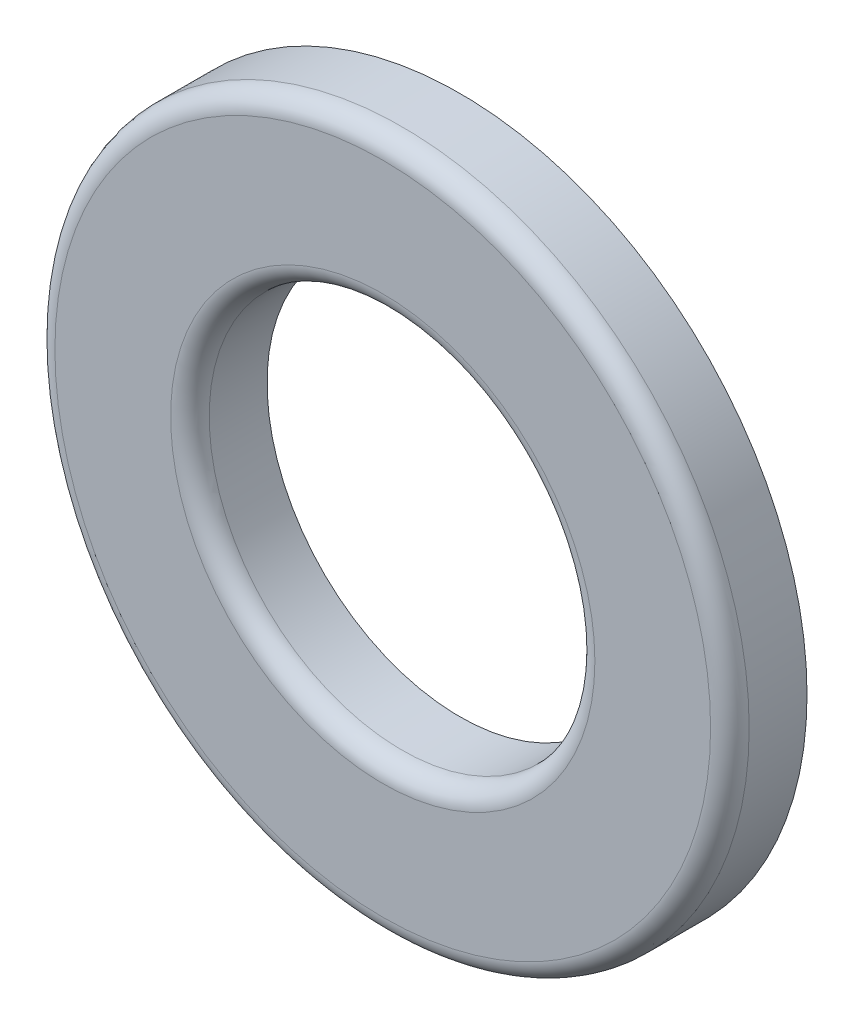
SolidWorks part; units mm, degrees
material "Chrome Stainless Steel"
ref_plane "Front Plane" through (0, 0, 0) normal (0, 0, 1) x (1, 0, 0)
ref_plane "Top Plane" through (0, 0, 0) normal (0, 1, 0) x (1, 0, 0)
ref_plane "Right Plane" through (0, 0, 0) normal (1, 0, 0) x (0, 0, -1)
sketch "Sketch1" plane through (0, 0, 0) normal (0, 0, 1) x (1, 0, 0)
  circle A0 centre (0, 0) radius 2.5
  circle A1 centre (0, 0) radius 4.5
  dimension "D1" = 5
  dimension "D2" = 9
extrude "Boss-Extrude1" add sketch "Sketch1" along normal blind 1
fillet "Fillet1" radius 0.25 2 edges at (2.5, 0, 1) (4.5, 0, 1)
